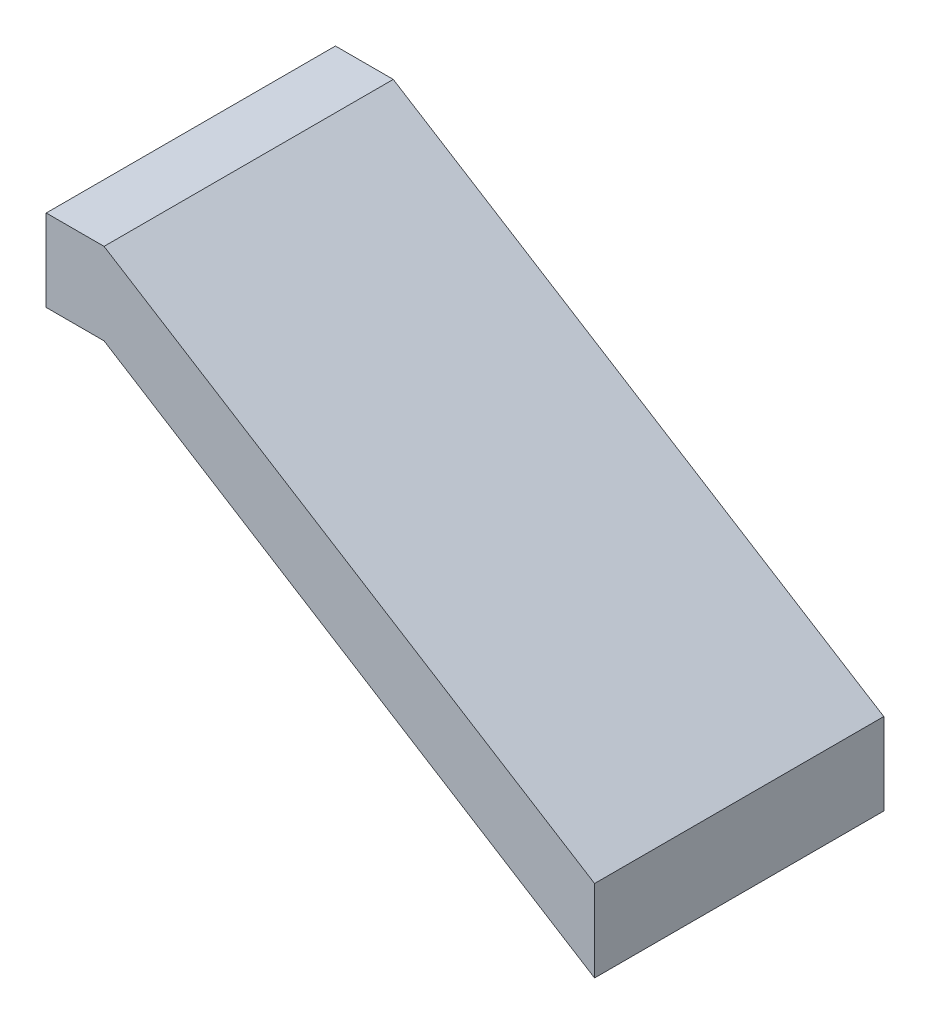
SolidWorks part; units mm, degrees
ref_plane "前视基准面" through (0, 0, 0) normal (0, 0, 1) x (1, 0, 0)
ref_plane "上视基准面" through (0, 0, 0) normal (0, 1, 0) x (1, 0, 0)
ref_plane "右视基准面" through (0, 0, 0) normal (1, 0, 0) x (0, 0, -1)
other "Configuration Table"
sketch "草图1" plane through (0, 0, 0) normal (0, 0, 1) x (1, 0, 0)
  line L0 (50, 609.9193) -> (150, 609.9193)
  line L1 (150, 609.9193) -> (998.0481, 80)
  line L2 (998.0481, 80) -> (998.0481, 221.5014)
  line L3 (998.0481, 221.5014) -> (150, 751.4207)
  line L4 (150, 751.4207) -> (50, 751.4207)
  line L5 (50, 751.4207) -> (50, 609.9193)
extrude "Active_sand_layer_normal_120" add sketch "草图1" along normal blind 500 separate body
